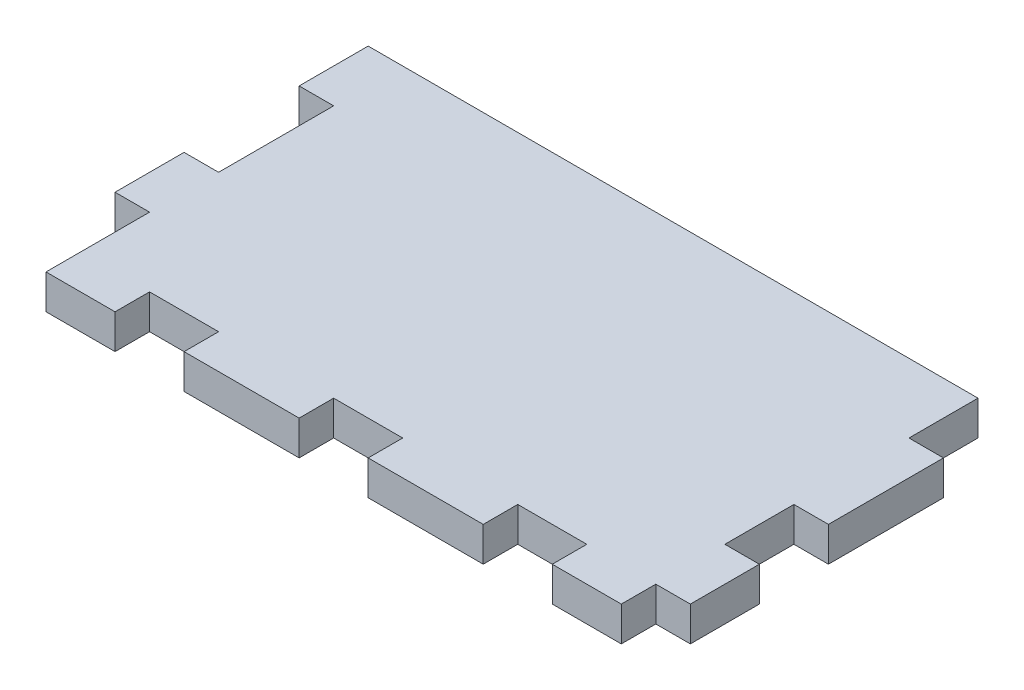
SolidWorks part; units mm, degrees
material "Acrylic (Medium-high impact)"
ref_plane "Front Plane" through (0, 0, 0) normal (0, 0, 1) x (1, 0, 0)
ref_plane "Top Plane" through (0, 0, 0) normal (0, 1, 0) x (1, 0, 0)
ref_plane "Right Plane" through (0, 0, 0) normal (1, 0, 0) x (0, 0, -1)
sketch "Sketch1" plane through (0, 0, 0) normal (0, 1, 0) x (1, 0, 0)
  line L0 (-44, 51.5) -> (-38, 51.5) construction
  line L1 (0, 0) -> (-50, 0)
  line L2 (0, 0) -> (0, 50)
  line L3 (0, 50) -> (-50, 50)
  line L4 (-50, 0) -> (-50, 50)
  line L5 (-50, 50) -> (-44, 50)
  line L6 (-50, 50) -> (-50, 53)
  line L7 (-50, 53) -> (-44, 53)
  line L8 (-44, 50) -> (-44, 53)
  line L9 (-38, 50) -> (-28, 50)
  line L10 (-38, 50) -> (-38, 53)
  line L11 (-38, 53) -> (-28, 53)
  line L12 (-28, 50) -> (-28, 53)
  line L13 (-22, 50) -> (-12, 50)
  line L14 (-22, 50) -> (-22, 53)
  line L15 (-22, 53) -> (-12, 53)
  line L16 (-12, 50) -> (-12, 53)
  line L17 (0, 50) -> (-6, 50)
  line L18 (0, 50) -> (0, 53)
  line L19 (0, 53) -> (-6, 53)
  line L20 (-6, 50) -> (-6, 53)
  line L21 (-50, 0) -> (-53, 0) construction
  line L22 (-50, 0) -> (-50, 6)
  line L23 (-50, 6) -> (-53, 6)
  line L25 (-50, 12) -> (-53, 12)
  line L26 (-50, 12) -> (-50, 22)
  line L27 (-50, 22) -> (-53, 22)
  line L29 (-50, 28) -> (-53, 28)
  line L30 (-50, 28) -> (-50, 38)
  line L31 (-50, 38) -> (-53, 38)
  line L33 (-50, 50) -> (-53, 50) construction
  line L34 (-50, 50) -> (-50, 44)
  line L35 (-50, 44) -> (-53, 44)
  line L37 (-28, 51.5) -> (-22, 51.5) construction
  line L38 (-12, 51.5) -> (-6, 51.5) construction
  line L39 (-51.5, 12) -> (-51.5, 22) construction
  line L40 (-51.5, 38) -> (-51.5, 28) construction
  line L42 (-25, 50) -> (-25, 0) construction
  line L43 (-50, 25) -> (0, 25) construction
  line L44 (0, -3) -> (-6, -3)
  line L45 (-6, 0) -> (-6, -3)
  line L46 (0, 0) -> (-6, 0)
  line L47 (0, 0) -> (0, -3)
  line L48 (-22, -3) -> (-12, -3)
  line L49 (-12, 0) -> (-12, -3)
  line L50 (-22, 0) -> (-12, 0)
  line L51 (-22, 0) -> (-22, -3)
  line L52 (-38, -3) -> (-28, -3)
  line L53 (-28, 0) -> (-28, -3)
  line L54 (-38, 0) -> (-28, 0)
  line L55 (-38, 0) -> (-38, -3)
  line L56 (-50, -3) -> (-44, -3)
  line L57 (-44, 0) -> (-44, -3)
  line L58 (-50, 0) -> (-44, 0)
  line L59 (-50, 0) -> (-50, -3)
  line L60 (0, 6) -> (3, 6)
  line L61 (3, 0) -> (3, 6)
  line L62 (0, 0) -> (3, 0)
  line L63 (0, 0) -> (0, 6)
  line L64 (0, 22) -> (3, 22)
  line L65 (3, 12) -> (3, 22)
  line L66 (0, 12) -> (3, 12)
  line L67 (0, 12) -> (0, 22)
  line L68 (0, 38) -> (3, 38)
  line L69 (3, 28) -> (3, 38)
  line L70 (0, 28) -> (3, 28)
  line L71 (0, 28) -> (0, 38)
  line L72 (0, 44) -> (3, 44)
  line L73 (3, 50) -> (3, 44)
  line L74 (0, 50) -> (3, 50)
  line L75 (0, 50) -> (0, 44)
  line L76 (-53, 44) -> (-53, 38)
  line L77 (-53, 28) -> (-53, 22)
  line L78 (-53, 12) -> (-53, 6)
  point P43 (-51.5, 0)
  dimension "D1" = 50
  dimension "D2" = 3
  dimension "D3" = 6
  dimension "D4" = 10
  dimension "D5" = 6
  dimension "D6" = 6
  dimension "D7" = 6
extrude "Boss-Extrude1" add sketch "Sketch1" along normal blind 3
sketch "Sketch2" plane through (0, 3, 0) normal (0, 1, 0) x (1, 0, 0)
  line L0 (-38, 53) -> (-28, 53) construction
  line L1 (-53, 53) -> (3, 53)
  line L2 (-53, 53) -> (-53, 28)
  line L3 (-53, 28) -> (3, 28)
  line L4 (3, 53) -> (3, 28)
  point P4 (0, 0)
  point P6 (0, 0)
  point P10 (-33, 53)
extrude "Cut-Extrude1" cut sketch "Sketch2" against normal through all
